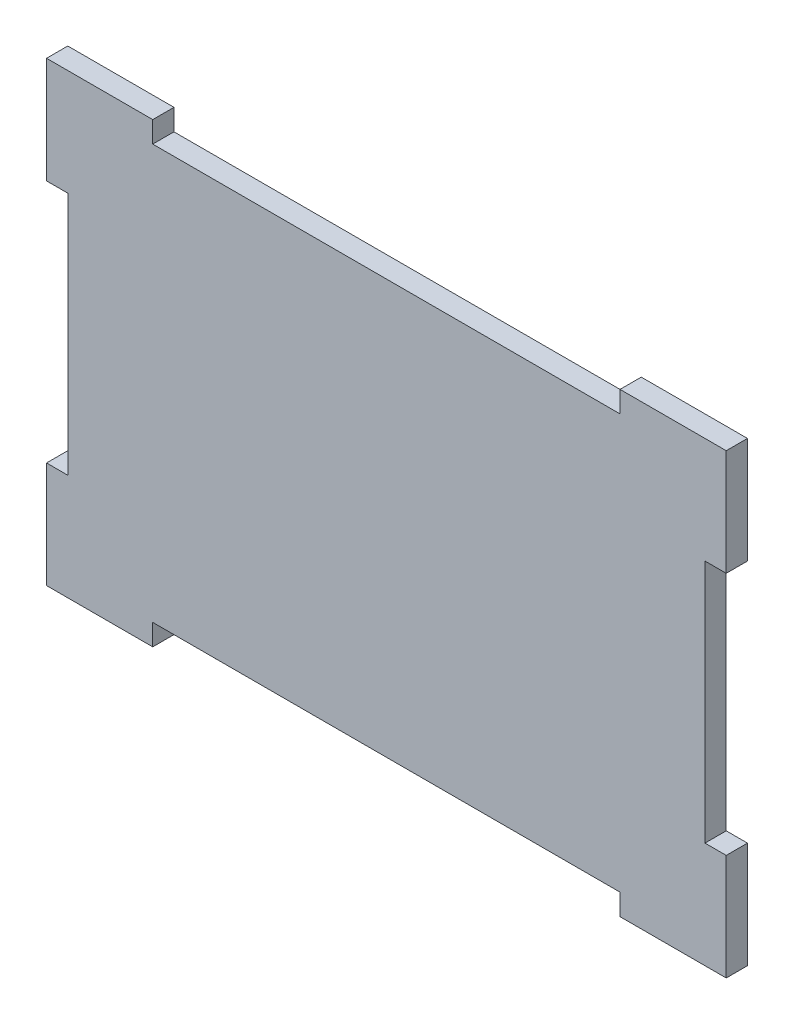
SolidWorks part; units mm, degrees
ref_plane "Front Plane" through (0, 0, 0) normal (0, 0, 1) x (1, 0, 0)
ref_plane "Top Plane" through (0, 0, 0) normal (0, 1, 0) x (1, 0, 0)
ref_plane "Right Plane" through (0, 0, 0) normal (1, 0, 0) x (0, 0, -1)
sketch "Sketch1" plane through (0, 0, 0) normal (0, 0, 1) x (1, 0, 0)
  line L0 (0, 0) -> (0, 20)
  line L1 (0, 66) -> (4, 66)
  line L2 (4, 66) -> (4, 20)
  line L3 (4, 20) -> (0, 20)
  line L4 (0, 66) -> (0, 86)
  line L5 (0, 86) -> (20, 86)
  line L6 (20, 86) -> (20, 82)
  line L7 (20, 82) -> (108, 82)
  line L8 (108, 82) -> (108, 86)
  line L9 (108, 86) -> (128, 86)
  line L10 (128, 86) -> (128, 66)
  line L11 (128, 66) -> (124, 66)
  line L12 (124, 66) -> (124, 20)
  line L13 (124, 20) -> (128, 20)
  line L14 (128, 20) -> (128, 0)
  line L15 (128, 0) -> (108, 0)
  line L16 (108, 0) -> (108, 4)
  line L17 (108, 4) -> (20, 4)
  line L18 (20, 4) -> (20, 0)
  line L19 (20, 0) -> (0, 0)
  dimension "D1" = 128
  dimension "D2" = 4
  dimension "D3" = 4
  dimension "D4" = 4
  dimension "D5" = 4
  dimension "D6" = 88
  dimension "D7" = 20
  dimension "D8" = 46
  dimension "D9" = 78
  dimension "D10" = 20
extrude "Boss-Extrude1" add sketch "Sketch1" along normal blind 4
